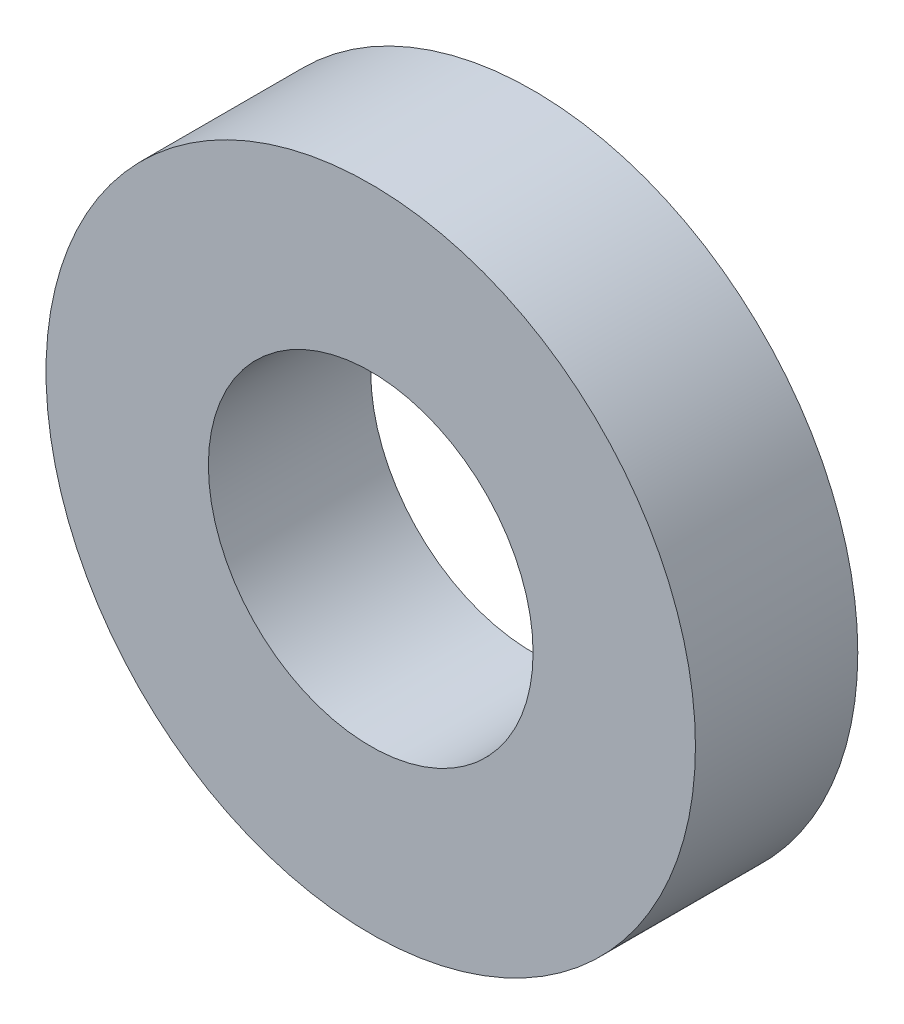
SolidWorks part; units mm, degrees
ref_plane "前视基准面" through (0, 0, 0) normal (0, 0, 1) x (1, 0, 0)
ref_plane "上视基准面" through (0, 0, 0) normal (0, 1, 0) x (1, 0, 0)
ref_plane "右视基准面" through (0, 0, 0) normal (1, 0, 0) x (0, 0, -1)
sketch "草图1" plane through (0, 0, 0) normal (0, 0, 1) x (1, 0, 0)
  circle A0 centre (0, 0) radius 4
  circle A1 centre (0, 0) radius 2
  dimension "D1" = 4
  dimension "D2" = 8
extrude "凸台-拉伸1" add sketch "草图1" along normal blind 2
